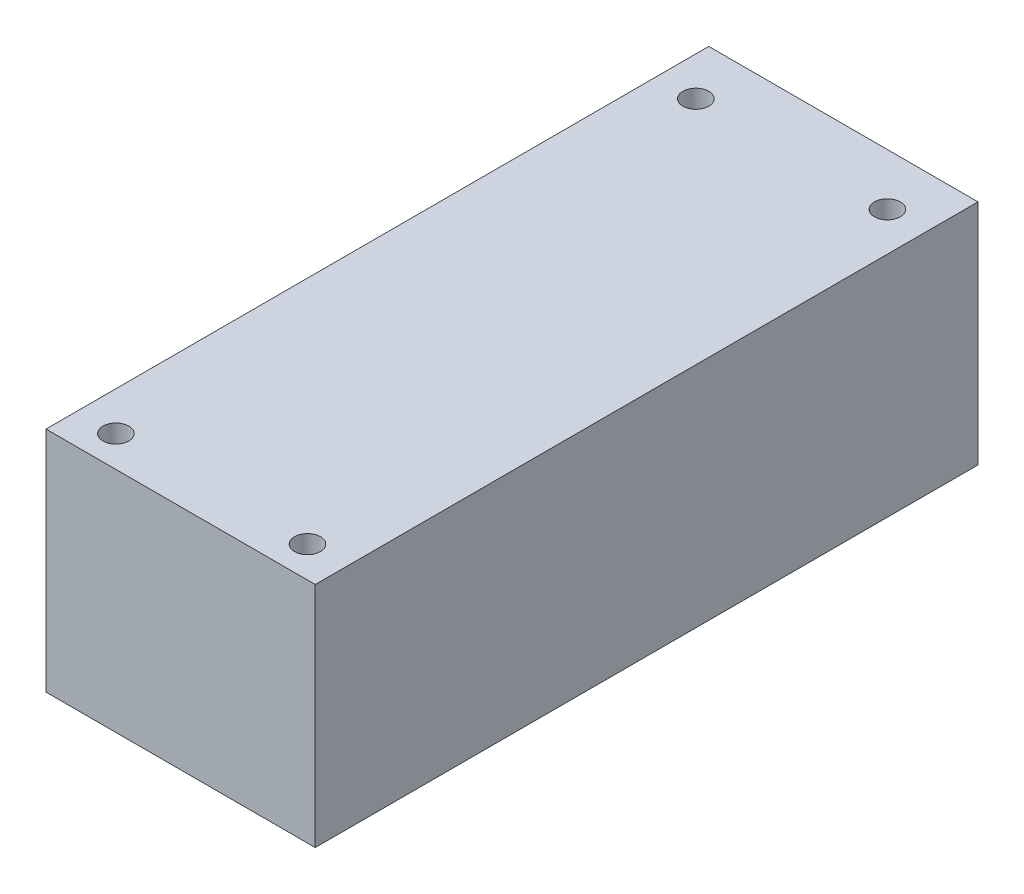
SolidWorks part; units mm, degrees
ref_plane "前视基准面" through (0, 0, 0) normal (0, 0, 1) x (1, 0, 0)
ref_plane "上视基准面" through (0, 0, 0) normal (0, 1, 0) x (1, 0, 0)
ref_plane "右视基准面" through (0, 0, 0) normal (1, 0, 0) x (0, 0, -1)
sketch "草图1" plane through (0, 0, 0) normal (0, 0, 1) x (1, 0, 0)
  line L0 (0, 30.199) -> (0, -24.5864) construction
  line L1 (-32.0838, 0) -> (36.6073, 0) construction
  line L2 (13, 11) -> (-13, 11)
  line L3 (-13, 11) -> (-13, -11)
  line L4 (13, 11) -> (13, -11)
  line L5 (13, -11) -> (-13, -11)
  point P5 (0, -11)
  point P10 (0, 11)
  point P12 (13, 0)
  point P13 (-13, 0)
  dimension "D1" = 22
  dimension "D2" = 26
extrude "凸台-拉伸1" add sketch "草图1" along normal mid plane 64
sketch "草图2" plane through (0, 11, 0) normal (0, 1, 0) x (1, 0, 0)
  line L0 (0, 34.1672) -> (0, -35.2948) construction
  line L1 (13, -32) -> (-13, -32) construction
  circle A0 centre (9.25, -29) radius 1.25
  circle A1 centre (9.25, 27) radius 1.25
  circle A2 centre (-9.25, 27) radius 1.25
  circle A3 centre (-9.25, -29) radius 1.25
  dimension "D4" = 2.5
  dimension "D5" = 2.5
  dimension "D1" = 3
  dimension "D2" = 56
  dimension "D3" = 9.25
extrude "切除-拉伸1" cut sketch "草图2" against normal blind 40
